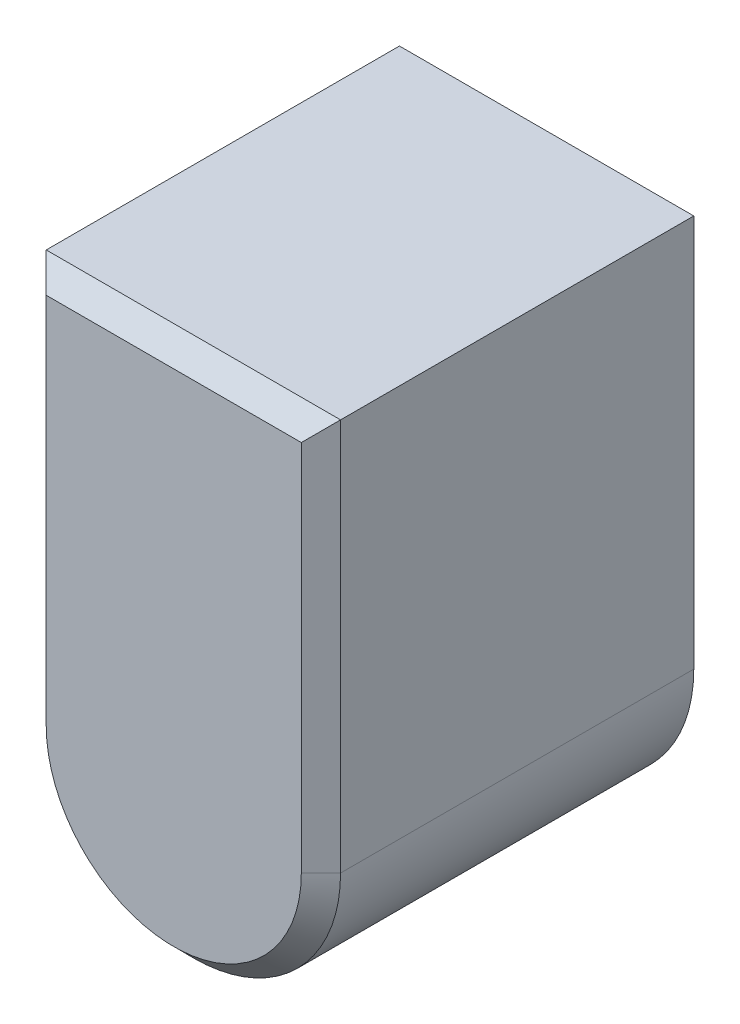
SolidWorks part; units mm, degrees
ref_plane "前视基准面" through (0, 0, 0) normal (0, 0, 1) x (1, 0, 0)
ref_plane "上视基准面" through (0, 0, 0) normal (0, 1, 0) x (1, 0, 0)
ref_plane "右视基准面" through (0, 0, 0) normal (1, 0, 0) x (0, 0, -1)
sketch "草图1" plane through (0, 0, 0) normal (0, 0, 1) x (1, 0, 0)
  line L0 (0, -2) -> (0, 2) construction
  line L1 (-1.5, -2) -> (-1.5, 2)
  line L2 (1.5, -2) -> (1.5, 2)
  arc A0 (-1.5, -2) -> (1.5, -2) centre (0, -2) ccw
  arc A1 (1.5, 2) -> (-1.5, 2) centre (0, 2) ccw
  point P2 (0, 0)
  dimension "D1" = 3
  dimension "D2" = 4
extrude "凸台-拉伸1" add sketch "草图1" along normal blind 4
sketch "草图2" plane through (0, 0, 4) normal (0, 0, 1) x (1, 0, 0)
  line L0 (-1.5, 2) -> (1.5, 2)
  arc A0 (1.5, 2) -> (-1.5, 2) centre (0, 2) ccw
  arc A1 (1.5, 2) -> (-1.5, 2) centre (0, 2) ccw construction
  arc A2 (-1.5, 2) -> (1.5, 2) centre (0, 2) ccw construction
extrude "切除-拉伸1" cut sketch "草图2" against normal up to next
chamfer "倒角1" distance 0.2 angle 45 8 edges at (0, -3.5, 0) (1.5, 0, 0) (0, 2, 0) (-1.5, 0, 0) (0, -3.5, 4) (1.5, 0, 4) (-1.5, 0, 4) (0, 2, 4)
